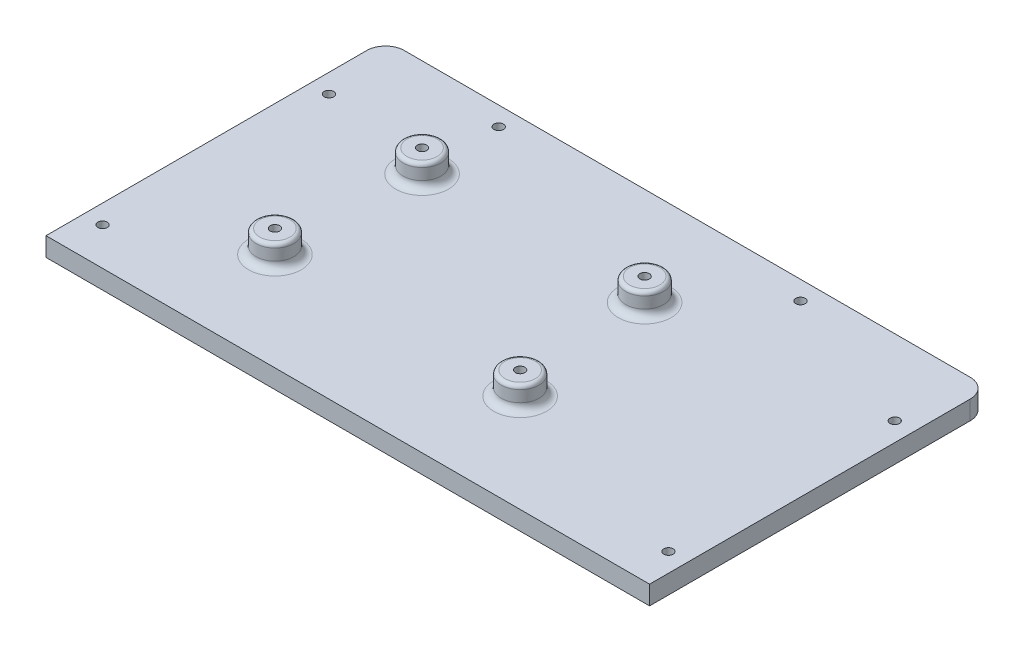
SolidWorks part; units mm, degrees
material "ABS"
ref_plane "Front Plane" through (0, 0, 0) normal (0, 0, 1) x (1, 0, 0)
ref_plane "Top Plane" through (0, 0, 0) normal (0, 1, 0) x (1, 0, 0)
ref_plane "Right Plane" through (0, 0, 0) normal (1, 0, 0) x (0, 0, -1)
sketch "Sketch1" plane through (0, 0, 0) normal (0, 1, 0) x (1, 0, 0)
  line L0 (101.6, 0) -> (101.6, 191.7492) construction
  line L1 (0, 0) -> (203.2, 0)
  line L2 (0, 0) -> (0, 107.95)
  line L3 (6.35, 114.3) -> (196.85, 114.3)
  line L4 (203.2, 0) -> (203.2, 107.95)
  circle A0 centre (6.35, 12.7) radius 1.5875
  circle A1 centre (196.85, 88.9) radius 1.5875
  circle A2 centre (6.35, 88.9) radius 1.5875
  circle A3 centre (44.45, 107.95) radius 1.5875
  circle A4 centre (146.05, 107.95) radius 1.5875
  circle A5 centre (196.85, 12.7) radius 1.5875
  arc A6 (196.85, 114.3) -> (203.2, 107.95) centre (196.85, 107.95) cw
  arc A7 (0, 107.95) -> (6.35, 114.3) centre (6.35, 107.95) cw
  point P9 (0, 114.3)
  point P24 (0, 114.3)
  dimension "D3" = 6.35
  dimension "D4" = 3.175
  dimension "D1" = 114.3
  dimension "D2" = 203.2
  dimension "D5" = 6.35
  dimension "D6" = 12.7
  dimension "D7" = 76.2
  dimension "D8" = 6.35
  dimension "D9" = 57.15
  dimension "D10" = 101.6
extrude "Boss-Extrude1" add sketch "Sketch1" along normal blind 6.35
sketch "Sketch2" plane through (0, 6.35, 0) normal (0, 1, 0) x (1, 0, 0)
  circle A0 centre (45.2951, 81.307) radius 6.35
  circle A1 centre (120.2251, 81.307) radius 6.35
  circle A2 centre (44.0251, 33.047) radius 6.35
  circle A3 centre (126.5751, 33.047) radius 6.35
  dimension "D1" = 12.7
  dimension "D2" = 74.93
  dimension "D3" = 48.26
  dimension "D4" = 1.27
  dimension "D5" = 82.55
extrude "Boss-Extrude2" add sketch "Sketch2" along normal blind 7.62
fillet "Fillet1" radius 2.54 4 edges at (126.5751, 6.35, -39.397) (120.2251, 6.35, -87.657) (45.2951, 6.35, -87.657) (44.0251, 6.35, -39.397)
fillet "Fillet2" radius 1.27 4 edges at (44.0251, 13.97, -26.697) (45.2951, 13.97, -74.957) (126.5751, 13.97, -26.697) (120.2251, 13.97, -74.957)
sketch "Sketch5" plane through (0, 13.97, 0) normal (0, 1, 0) x (1, 0, 0)
  circle A1 centre (45.2951, 81.307) radius 1.5875
  circle A2 centre (120.2251, 81.307) radius 1.5875
  circle A3 centre (126.5751, 33.047) radius 1.5875
  circle A4 centre (44.0251, 33.047) radius 1.5875
  dimension "D1" = 3.175
extrude "Cut-Extrude1" cut sketch "Sketch5" against normal through all
